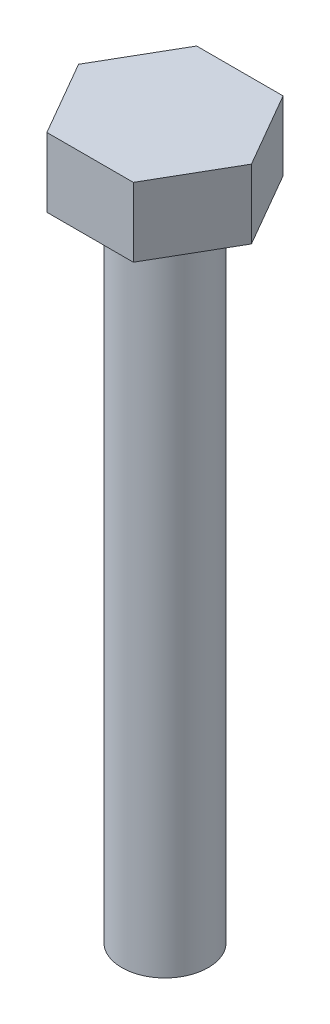
SolidWorks part; units mm, degrees
material "Alliage 1060"
ref_plane "Plan de face" through (0, 0, 0) normal (0, 0, 1) x (1, 0, 0)
ref_plane "Plan de dessus" through (0, 0, 0) normal (0, 1, 0) x (1, 0, 0)
ref_plane "Plan de droite" through (0, 0, 0) normal (1, 0, 0) x (0, 0, -1)
sketch "Esquisse1" plane through (0, 0, 0) normal (0, 1, 0) x (1, 0, 0)
  circle A0 centre (0, 0) radius 5
  dimension "D1" = 10
extrude "Boss.-Extru.1" add sketch "Esquisse1" along normal blind 75
sketch "Esquisse2" plane through (0, 75, 0) normal (0, 1, 0) x (1, 0, 0)
  line L0 (-5, 8.6603) -> (5, 8.6603)
  line L1 (5, 8.6603) -> (10, 0)
  line L2 (10, 0) -> (5, -8.6603)
  line L3 (5, -8.6603) -> (-5, -8.6603)
  line L4 (-5, -8.6603) -> (-10, 0)
  line L5 (-10, 0) -> (-5, 8.6603)
  point P6 (0, 0)
  point P7 (0, 8.6603)
  dimension "D1" = 120
  dimension "D2" = 120
  dimension "D3" = 10
extrude "Boss.-Extru.2" add sketch "Esquisse2" along normal blind 8
sketch "Esquisse4" plane through (0, 0, 0) normal (0, -1, 0) x (1, 0, 0)
  circle A0 centre (0, 0) radius 5
  dimension "D1" = 10
